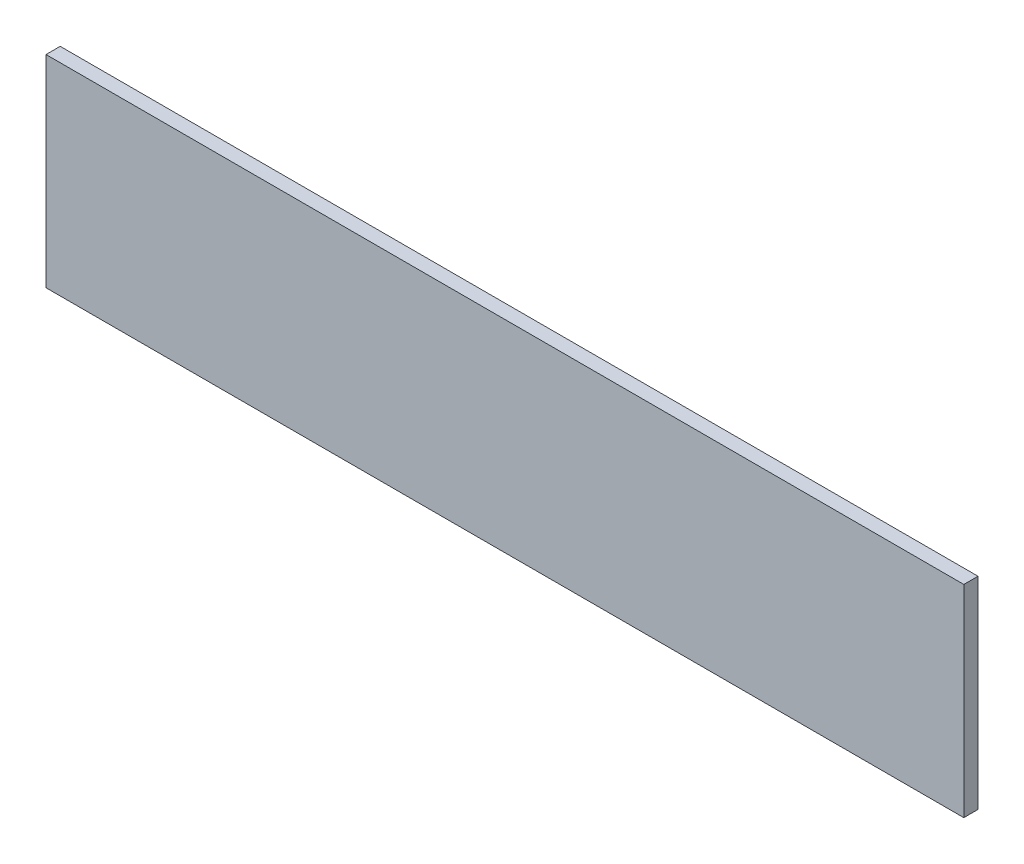
SolidWorks part; units mm, degrees
ref_plane "Front Plane" through (0, 0, 0) normal (0, 0, 1) x (1, 0, 0)
ref_plane "Top Plane" through (0, 0, 0) normal (0, 1, 0) x (1, 0, 0)
ref_plane "Right Plane" through (0, 0, 0) normal (1, 0, 0) x (0, 0, -1)
sketch "Sketch1" plane through (0, 0, 0) normal (0, 0, 1) x (1, 0, 0)
  line L1 (0, 0) -> (388, 0)
  line L2 (0, 0) -> (0, 85.4)
  line L3 (0, 85.4) -> (388, 85.4)
  line L4 (388, 0) -> (388, 85.4)
  dimension "D1" = 85.4
  dimension "D2" = 388
extrude "Boss-Extrude1" add sketch "Sketch1" along normal blind 6
